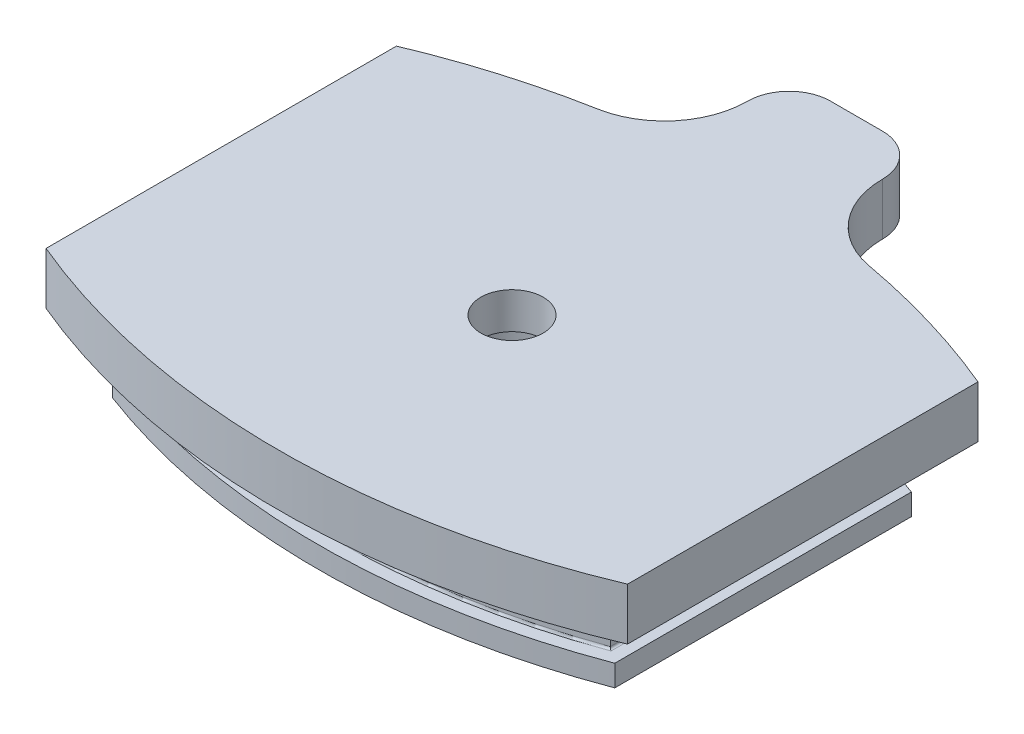
SolidWorks part; units mm, degrees
ref_plane "Front Plane" through (0, 0, 0) normal (0, 0, 1) x (1, 0, 0)
ref_plane "Top Plane" through (0, 0, 0) normal (0, 1, 0) x (1, 0, 0)
ref_plane "Right Plane" through (0, 0, 0) normal (1, 0, 0) x (0, 0, -1)
sketch "Sketch1" plane through (0, 0, 0) normal (0, 1, 0) x (1, 0, 0)
  line L0 (-35.56, 21.4311) -> (-35.56, -21.4311)
  line L1 (35.56, 21.4311) -> (35.56, -21.4311)
  arc A0 (-35.56, -21.4311) -> (35.56, -21.4311) centre (0, 63.5) ccw
  arc A1 (35.56, 21.4311) -> (-35.56, 21.4311) centre (0, -63.5) ccw
  dimension "D3" = 184.15
  dimension "D1" = 63.5
  dimension "D2" = 63.5
  dimension "D4" = 35.56
  dimension "D5" = 35.56
extrude "Boss-Extrude1" add sketch "Sketch1" against normal blind 6.35
sketch "Sketch2" plane through (0, -6.35, 0) normal (0, -1, 0) x (1, 0, 0)
  line L4 (30.7086, -18.1391) -> (30.7086, 18.1391)
  line L5 (-30.7086, 18.1391) -> (-30.7086, -18.1391)
  line L6 (30.7086, -18.1391) -> (30.7086, 18.1391)
  line L7 (-30.7086, 18.1391) -> (-30.7086, -18.1391)
  arc A4 (-30.7086, -18.1391) -> (30.7086, -18.1391) centre (0, 63.5) ccw
  arc A5 (30.7086, 18.1391) -> (-30.7086, 18.1391) centre (0, -63.5) ccw
  arc A6 (-30.7086, -18.1391) -> (30.7086, -18.1391) centre (0, 63.5) ccw
  arc A7 (30.7086, 18.1391) -> (-30.7086, 18.1391) centre (0, -63.5) ccw
  dimension "D1" = 4.8514
extrude "Boss-Extrude2" add sketch "Sketch2" along normal blind 8.7122
sketch "Sketch3" plane through (0, -6.35, 0) normal (0, -1, 0) x (1, 0, 0)
  line L2 (-35.56, -21.4311) -> (-35.56, 21.4311) construction
  line L3 (-35.56, 28.575) -> (35.56, 28.575)
  line L4 (28.9306, -16.8988) -> (28.9306, 16.8988)
  line L5 (-28.9306, 16.8988) -> (-28.9306, -16.8988)
  line L6 (28.9306, -16.8988) -> (28.9306, 16.8988)
  line L7 (-28.9306, 16.8988) -> (-28.9306, -16.8988)
  line L8 (-35.56, 28.575) -> (-35.56, -28.575)
  line L9 (-35.56, -28.575) -> (35.56, -28.575)
  line L10 (35.56, 28.575) -> (35.56, -28.575)
  line L11 (35.56, 21.4311) -> (35.56, -21.4311) construction
  arc A2 (-35.56, -21.4311) -> (35.56, -21.4311) centre (0, 63.5) ccw construction
  arc A3 (35.56, 21.4311) -> (-35.56, 21.4311) centre (0, -63.5) ccw construction
  arc A4 (-28.9306, -16.8988) -> (28.9306, -16.8988) centre (0, 63.5) ccw
  arc A5 (28.9306, 16.8988) -> (-28.9306, 16.8988) centre (0, -63.5) ccw
  arc A6 (-28.9306, -16.8988) -> (28.9306, -16.8988) centre (0, 63.5) ccw
  arc A7 (28.9306, 16.8988) -> (-28.9306, 16.8988) centre (0, -63.5) ccw
  dimension "D1" = 1.778
extrude "Cut-Extrude1" cut sketch "Sketch3" along normal blind 3.556 from offset 2.54
sketch "Sketch4" plane through (0, -15.0622, 0) normal (0, -1, 0) x (1, 0, 0)
  point P0 (0, 0)
hole_wizard "Hole1" positions "Sketch5" profile "Sketch6" legacy
sketch "Sketch5" plane through (0, -15.0622, 0) normal (0, -1, 0) x (-1, 0, 0)
  point P0 (0, 0)
sketch "Sketch6" plane through (0, -15.0622, 0) normal (1, 0, 0) x (0, 0, -1)
  line L0 (0, 0) -> (0, 15.0622)
  line L1 (0, 15.0622) -> (3.81, 15.0622)
  line L2 (3.81, 15.0622) -> (3.81, 0)
  line L3 (3.81, 0) -> (0, 0)
  line L4 (0, 110) -> (0, -10) construction
  dimension "Diameter" = 7.62
  dimension "Depth" = 15.0622
sketch "Sketch7" plane through (0, -15.0622, 0) normal (0, -1, 0) x (1, 0, 0)
  line L6 (25.6286, -14.5432) -> (25.6286, 14.5432)
  line L7 (-25.6286, 14.5432) -> (-25.6286, -14.5432)
  line L8 (25.6286, -14.5432) -> (25.6286, 14.5432)
  line L9 (-25.6286, 14.5432) -> (-25.6286, -14.5432)
  arc A6 (-25.6286, -14.5432) -> (25.6286, -14.5432) centre (0, 63.5) ccw
  arc A7 (25.6286, 14.5432) -> (-25.6286, 14.5432) centre (0, -63.5) ccw
  arc A8 (-25.6286, -14.5432) -> (25.6286, -14.5432) centre (0, 63.5) ccw
  arc A9 (25.6286, 14.5432) -> (-25.6286, 14.5432) centre (0, -63.5) ccw
  dimension "D1" = 5.08
extrude "Cut-Extrude2" cut sketch "Sketch7" against normal offset from surface (10.6172 mm away) 4.445 up to face at (0, 0, -3.81)
sketch "Sketch8" plane through (0, -4.445, 0) normal (0, -1, 0) x (1, 0, 0)
  line L1 (-11.43, 11.43) -> (11.43, 11.43)
  line L2 (-11.43, 11.43) -> (-11.43, -11.43)
  line L3 (-11.43, -11.43) -> (11.43, -11.43)
  line L4 (11.43, 11.43) -> (11.43, -11.43)
  line L5 (-11.43, 11.43) -> (11.43, -11.43) construction
  line L6 (-11.43, -11.43) -> (11.43, 11.43) construction
  line L7 (-8.89, 8.89) -> (8.89, 8.89)
  line L8 (-8.89, 8.89) -> (-8.89, -8.89)
  line L9 (-8.89, -8.89) -> (8.89, -8.89)
  line L10 (8.89, 8.89) -> (8.89, -8.89)
  line L11 (-8.89, 8.89) -> (8.89, -8.89) construction
  line L12 (-8.89, -8.89) -> (8.89, 8.89) construction
  circle A0 centre (0, 0) radius 3.81 construction
  point P0 (0, 0)
  point P8 (0, 0)
  dimension "D1" = 11.43
  dimension "D2" = 8.89
extrude "Boss-Extrude3" add sketch "Sketch8" along normal up to surface (10.6172 mm away) up to face at (0, -15.0622, 0)
fillet "Fillet1" radius 0.254 8 edges at (28.9306, -12.446, 0) (28.9306, -8.89, 0) (0, -12.446, -21.9456) (0, -8.89, -21.9456) (0, -8.89, 21.9456) (0, -12.446, 21.9456) (-28.9306, -12.446, 0) (-28.9306, -8.89, 0)
fillet "Fillet2" radius 6.604 4 edges at (-8.89, -9.7536, -8.89) (8.89, -9.7536, -8.89) (-8.89, -9.7536, 8.89) (8.89, -9.7536, 8.89)
fillet "Fillet3" radius 9.144 4 edges at (-11.43, -9.7536, 11.43) (11.43, -9.7536, 11.43) (-11.43, -9.7536, -11.43) (11.43, -9.7536, -11.43)
chamfer "Chamfer1" distance 1.016 angle 45 20 edges at (0, -15.0622, -18.6436) (25.6286, -15.0622, 0) (-25.6286, -15.0622, 0) (0, -15.0622, 18.6436) (8.7518, -15.0622, -8.7518) (0, -15.0622, -11.43) (-8.7518, -15.0622, -8.7518) (-11.43, -15.0622, 0) (-8.7518, -15.0622, 8.7518) (0, -15.0622, 11.43) (8.7518, -15.0622, 8.7518) (11.43, -15.0622, 0) (6.9557, -15.0622, -6.9557) (8.89, -15.0622, 0) (6.9557, -15.0622, 6.9557) (0, -15.0622, 8.89) (-6.9557, -15.0622, 6.9557) (-8.89, -15.0622, 0) (-6.9557, -15.0622, -6.9557) (0, -15.0622, -8.89)
sketch "Sketch9" plane through (0, 0, 0) normal (0, 1, 0) x (1, 0, 0)
  line L0 (-3.175, 37.0628) -> (3.175, 37.0628) construction
  line L1 (-18.415, 37.0628) -> (18.415, 37.0628) construction
  line L2 (-3.175, 42.1428) -> (3.175, 42.1428)
  arc A0 (35.56, 21.4311) -> (-35.56, 21.4311) centre (0, -63.5) ccw construction
  arc A1 (16.5849, 27.069) -> (-16.5849, 27.069) centre (0, -63.5) ccw
  arc A2 (-16.5849, 27.069) -> (-8.255, 37.0628) centre (-18.415, 37.0628) ccw
  arc A3 (-3.175, 42.1428) -> (-8.255, 37.0628) centre (-3.175, 37.0628) ccw
  arc A4 (8.255, 37.0628) -> (3.175, 42.1428) centre (3.175, 37.0628) ccw
  arc A5 (8.255, 37.0628) -> (16.5849, 27.069) centre (18.415, 37.0628) ccw
  point P11 (0, 37.0628)
  point P12 (0, 37.0628)
  dimension "D2" = 20.32
  dimension "D3" = 10.16
  dimension "D1" = 6.35
extrude "Boss-Extrude4" add sketch "Sketch9" against normal up to surface (6.35 mm away) up to face at (0, -6.35, 0)
